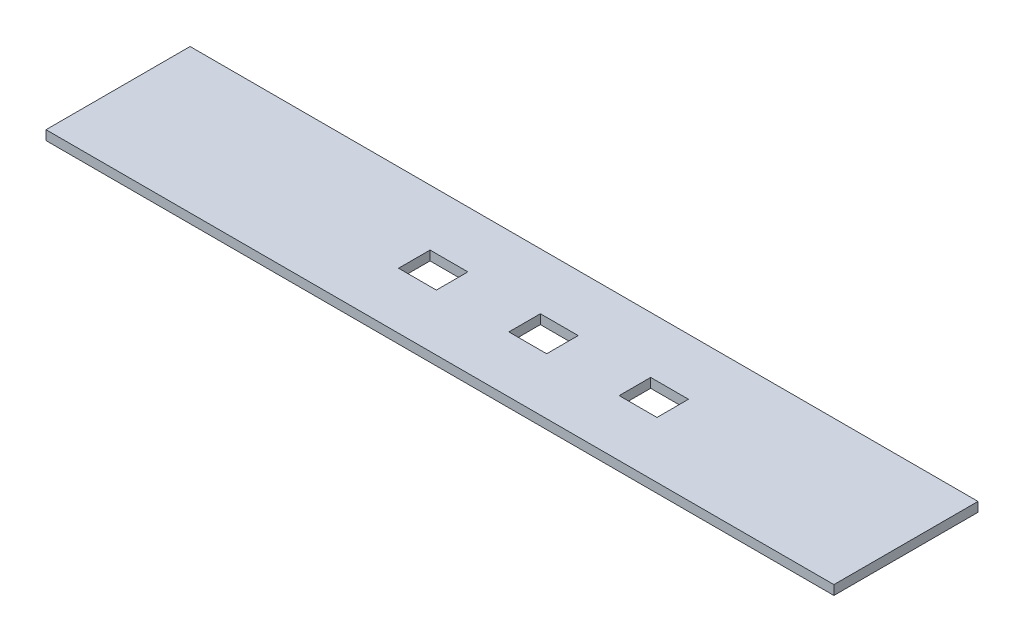
SolidWorks part; units mm, degrees
ref_plane "Front Plane" through (0, 0, 0) normal (0, 0, 1) x (1, 0, 0)
ref_plane "Top Plane" through (0, 0, 0) normal (0, 1, 0) x (1, 0, 0)
ref_plane "Right Plane" through (0, 0, 0) normal (1, 0, 0) x (0, 0, -1)
sketch "Sketch1" plane through (0, 0, 0) normal (0, 1, 0) x (1, 0, 0)
  line L1 (-125, 22.86) -> (125, 22.86)
  line L2 (-125, 22.86) -> (-125, -22.86)
  line L3 (-125, -22.86) -> (125, -22.86)
  line L4 (125, 22.86) -> (125, -22.86)
  line L5 (-125, 22.86) -> (125, -22.86) construction
  line L6 (-125, -22.86) -> (125, 22.86) construction
  point P0 (0, 0)
  dimension "D1" = 250
  dimension "D2" = 45.72
extrude "Boss-Extrude1" add sketch "Sketch1" along normal blind 3 contours L1 L4 L3 L2
sketch "Sketch2" plane through (0, 0, 0) normal (0, 1, 0) x (1, 0, 0)
  line L1 (-31, 5) -> (-19, 5)
  line L2 (-31, 5) -> (-31, -5)
  line L3 (-31, -5) -> (-19, -5)
  line L4 (-19, 5) -> (-19, -5)
  line L5 (-31, 5) -> (-19, -5) construction
  line L6 (-31, -5) -> (-19, 5) construction
  line L8 (4, 5) -> (16, 5)
  line L9 (4, 5) -> (4, -5)
  line L10 (4, -5) -> (16, -5)
  line L11 (16, 5) -> (16, -5)
  line L12 (4, 5) -> (16, -5) construction
  line L13 (4, -5) -> (16, 5) construction
  line L14 (39, 5) -> (51, 5)
  line L15 (39, 5) -> (39, -5)
  line L16 (39, -5) -> (51, -5)
  line L17 (51, 5) -> (51, -5)
  line L18 (39, 5) -> (51, -5) construction
  line L19 (39, -5) -> (51, 5) construction
  point P0 (-25, 0)
  point P5 (45, 0)
  point P8 (10, 0)
  dimension "D1" = 10
  dimension "D2" = 12
  dimension "D3" = 25
  dimension "D4" = 10
  dimension "D5" = 12
  dimension "D6" = 23
  dimension "D7" = 10
  dimension "D8" = 12
  dimension "D9" = 23
extrude "Cut-Extrude1" cut sketch "Sketch2" against normal through all both and the other way through all
